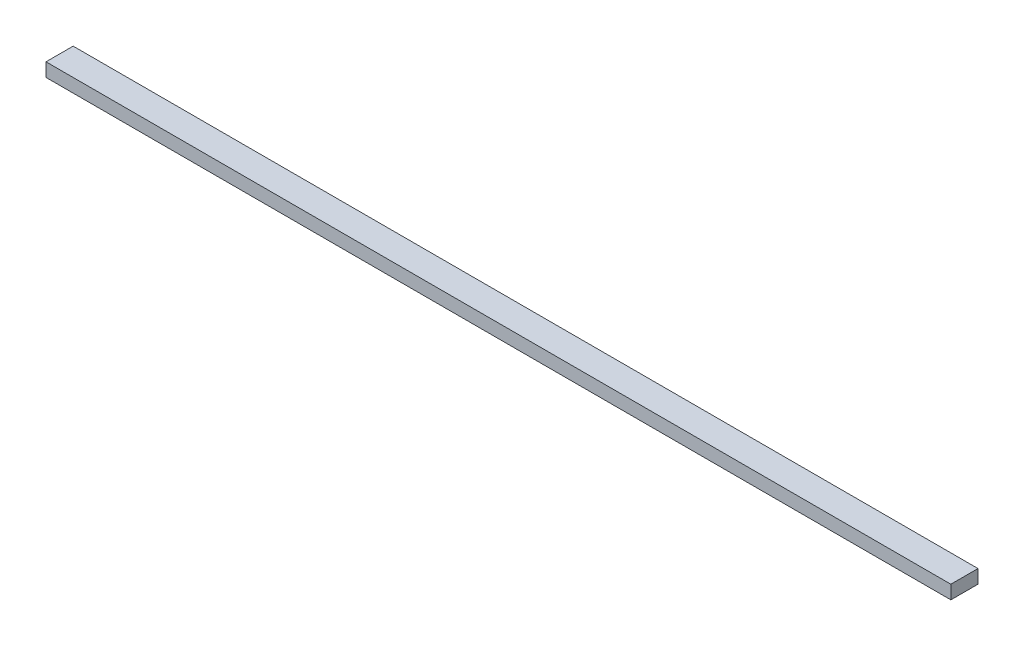
SolidWorks part; units mm, degrees
ref_plane "前视基准面" through (0, 0, 0) normal (0, 0, 1) x (1, 0, 0)
ref_plane "上视基准面" through (0, 0, 0) normal (0, 1, 0) x (1, 0, 0)
ref_plane "右视基准面" through (0, 0, 0) normal (1, 0, 0) x (0, 0, -1)
sketch "草图1" plane through (0, 0, 0) normal (0, 1, 0) x (1, 0, 0)
  line L1 (-100, -3) -> (100, -3)
  line L2 (-100, -3) -> (-100, 3)
  line L3 (-100, 3) -> (100, 3)
  line L4 (100, -3) -> (100, 3)
  line L5 (-100, -3) -> (100, 3) construction
  line L6 (-100, 3) -> (100, -3) construction
  point P0 (0, 0)
  dimension "D1" = 6
  dimension "D2" = 200
extrude "凸台-拉伸1" add sketch "草图1" along normal blind 3
